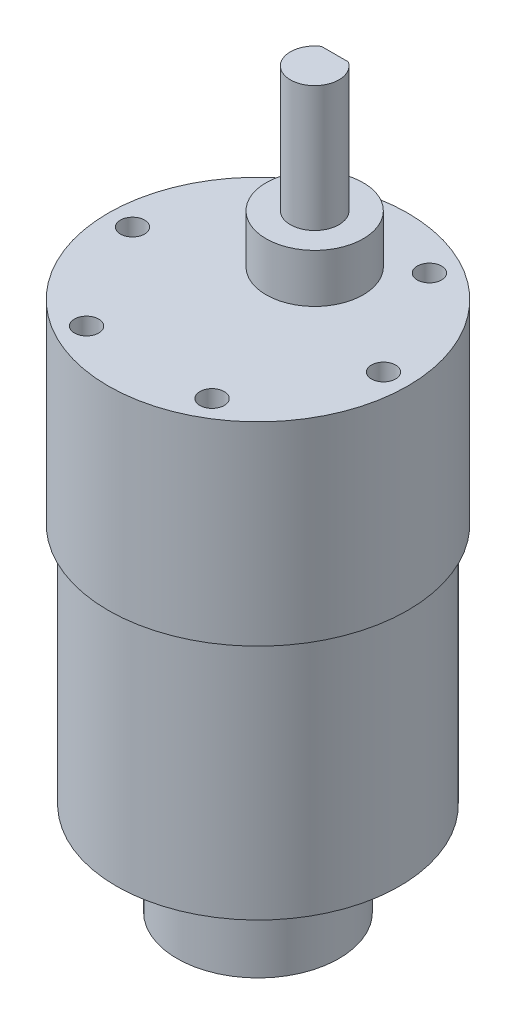
SolidWorks part; units mm, degrees
ref_plane "前视基准面" through (0, 0, 0) normal (0, 0, 1) x (1, 0, 0)
ref_plane "上视基准面" through (0, 0, 0) normal (0, 1, 0) x (1, 0, 0)
ref_plane "右视基准面" through (0, 0, 0) normal (1, 0, 0) x (0, 0, -1)
sketch "草图1" plane through (0, 0, 0) normal (0, 1, 0) x (1, 0, 0)
  circle A0 centre (0, 0) radius 18.5
  dimension "D1" = 37
extrude "凸台-拉伸1" add sketch "草图1" along normal blind 24
sketch "草图2" plane through (0, 24, 0) normal (0, 1, 0) x (1, 0, 0)
  line L0 (0, 13.459) -> (0, -9.4291) construction
  circle A0 centre (0, 7) radius 6
  dimension "D1" = 12
  dimension "D2" = 7
extrude "凸台-拉伸2" add sketch "草图2" along normal blind 6
sketch "草图3" plane through (0, 30, 0) normal (0, 1, 0) x (1, 0, 0)
  circle A0 centre (0, 7) radius 3
  circle A1 centre (0, 7) radius 6 construction
  dimension "D1" = 6
extrude "凸台-拉伸3" add sketch "草图3" along normal blind 15.5
sketch "草图4" plane through (0, 0, 0) normal (0, -1, 0) x (1, 0, 0)
  circle A0 centre (0, 0) radius 17.5
  dimension "D1" = 35
extrude "凸台-拉伸4" add sketch "草图4" along normal blind 30
sketch "草图5" plane through (0, -30, 0) normal (0, -1, 0) x (1, 0, 0)
  circle A0 centre (0, 0) radius 10
  dimension "D1" = 20
extrude "凸台-拉伸6" add sketch "草图5" along normal blind 11.5
sketch "草图6" plane through (0, 45.5, 0) normal (0, 1, 0) x (1, 0, 0)
  line L0 (-3.7113, 9.5) -> (4.0996, 9.5)
  arc A0 (4.0996, 9.5) -> (-3.7113, 9.5) centre (0.1941, 9.5) ccw
  dimension "D1" = 9.5
extrude "切除-拉伸1" cut sketch "草图6" against normal blind 12
sketch "草图7" plane through (0, 24, 0) normal (0, 1, 0) x (1, 0, 0)
  line L0 (-20.2014, 0) -> (20.0464, 0) construction
  circle A0 centre (-15.5, 0) radius 1.5
  circle A1 centre (-7.75, 13.4234) radius 1.5
  circle A2 centre (7.75, 13.4234) radius 1.5
  circle A3 centre (15.5, 0) radius 1.5
  circle A4 centre (7.75, -13.4234) radius 1.5
  circle A5 centre (-7.75, -13.4234) radius 1.5
  point P19 (0, 0)
  dimension "D1" = 6
  dimension "D3" = 3
  dimension "D2" = 15.5
extrude "切除-拉伸2" cut sketch "草图7" against normal blind 10
equation "\"11.5.00mm\"=115"
